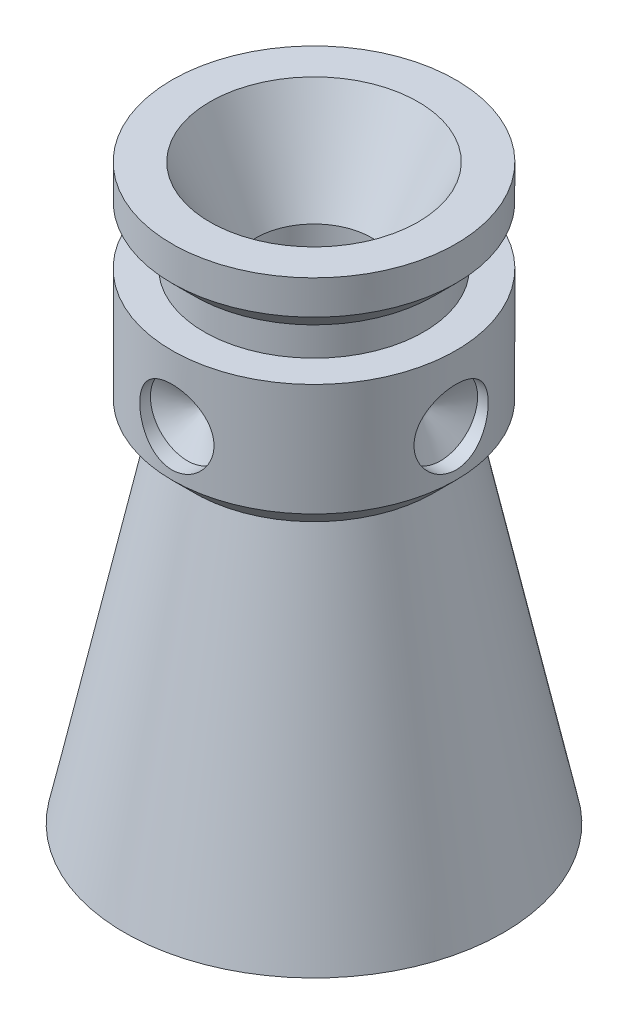
SolidWorks part; units mm, degrees
material "AISI 316 Annealed Stainless Steel Bar (SS)"
ref_plane "Front Plane" through (0, 0, 0) normal (0, 0, 1) x (1, 0, 0)
ref_plane "Top Plane" through (0, 0, 0) normal (0, 1, 0) x (1, 0, 0)
ref_plane "Right Plane" through (0, 0, 0) normal (1, 0, 0) x (0, 0, -1)
sketch "Sketch1" plane through (0, 0, 0) normal (0, 0, 1) x (1, 0, 0)
  line L20 (0, 0) -> (-9.525, 0) construction
  line L21 (0, 0) -> (0, -38.4163) construction
  line L37 (-6.424, -6.35) -> (-6.424, -8.89) construction
  line L38 (-6.424, -8.89) -> (-12.7, -38.4163) construction
  line L39 (-3.884, -6.35) -> (-3.884, 0) construction
  line L40 (-12.7, -38.4163) -> (-10.16, -38.4163)
  line L41 (-10.16, -38.4163) -> (-3.884, -8.89)
  line L42 (-3.884, -8.89) -> (-6.424, -8.89) construction
  line L43 (-3.884, -8.89) -> (-3.884, -6.35)
  line L46 (-10.16, -38.4163) -> (0, -38.4163) construction
  line L48 (-6.985, 0) -> (-3.884, -6.35)
  line L55 (-3.884, -6.35) -> (-9.525, -6.35) construction
  line L56 (-6.985, 0) -> (-9.525, 0)
  line L57 (-9.525, 0) -> (-9.525, -15.24) construction
  line L58 (-9.525, -3.81) -> (-7.366, -3.81)
  line L59 (-7.366, -3.81) -> (-7.366, -6.1913)
  line L60 (-7.366, -6.1913) -> (-9.525, -6.1913)
  line L61 (-9.525, 0) -> (-9.525, -3.81)
  line L63 (-9.525, -6.1913) -> (-9.525, -15.24)
  line L64 (-9.525, -15.24) -> (-7.7737, -15.24)
  line L65 (-12.7, -38.4163) -> (-7.7737, -15.24)
  dimension "D1" = 9.525
  dimension "D2" = 2.54
  dimension "D3" = 15.24
  dimension "D4" = 2.54
  dimension "D5" = 3.884
  dimension "D6" = 2.54
  dimension "D7" = 12
  dimension "D8" = 10.16
  dimension "D9" = 3.81
  dimension "D10" = 2.3813
  dimension "D11" = 7.366
  dimension "D12" = 6.35
revolve "Body" add sketch "Sketch1" angle 360 about L21
ref_plane "HolePlane" through (-9.525, 0, 0) normal (-1, 0, 0) x (0, 0, 1)
sketch "Sketch3" plane through (-9.525, 0, 0) normal (-1, 0, 0) x (0, 0, 1)
  line L0 (0, 0) -> (0, -10.6363)
  line L1 (9.525, -6.1912) -> (-9.525, -6.1912) construction
  point P6 (0, -10.6363)
  dimension "D1" = 4.445
hole_wizard "SetScrew" positions "Sketch3" profile "Sketch4" hole size "#9" standard "ANSI Inch"
sketch "Sketch4" plane through (-9.525, -10.6363, 0) normal (0, 1, 0) x (0, 0, 1)
  line L0 (0, 0) -> (0, 2.54)
  line L1 (0, 2.54) -> (2.4892, 1.0443)
  line L2 (2.4892, 1.0443) -> (2.4892, 0)
  line L5 (2.4892, 0) -> (0, 0)
  line L10 (0, 2.54) -> (-2.4892, 1.0443) construction
  line L11 (0, -6.35) -> (0, 107.95) construction
  dimension "Hole Dia." = 4.9784
  dimension "Hole Depth" = 2.54
  dimension "Drill Angle" = 118
pattern_circular "CirPattern1" count 4 over 360 about axis through (0, 0, 0) along (0, 1, 0) of "SetScrew"
sketch "Sketch7" plane through (-9.525, 0, 0) normal (-1, 0, 0) x (0, 0, 1)
  line L0 (-26.0666, -24.4142) -> (26.0666, -24.4142) construction
  line L1 (0, -24.4142) -> (0, 0) construction
  text T0 "Moses\r\nDilts" font "Blippo" height 6.35
  point P3 (0, -23.5315)
  point P5 (0, -24.4142)
wrap "Wrap6" [suppressed] sketch "Sketch7" source sketch "Sketch7" thickness 0.635 parameters "D1"=0.635
chamfer "Chamfer1" distance 1.524 angle 45 2 edges at (-9.525, -15.24, 0) (-9.525, -3.81, 0)
equation "\"dt\"=0.1"
equation "\"w\"=0.1"
